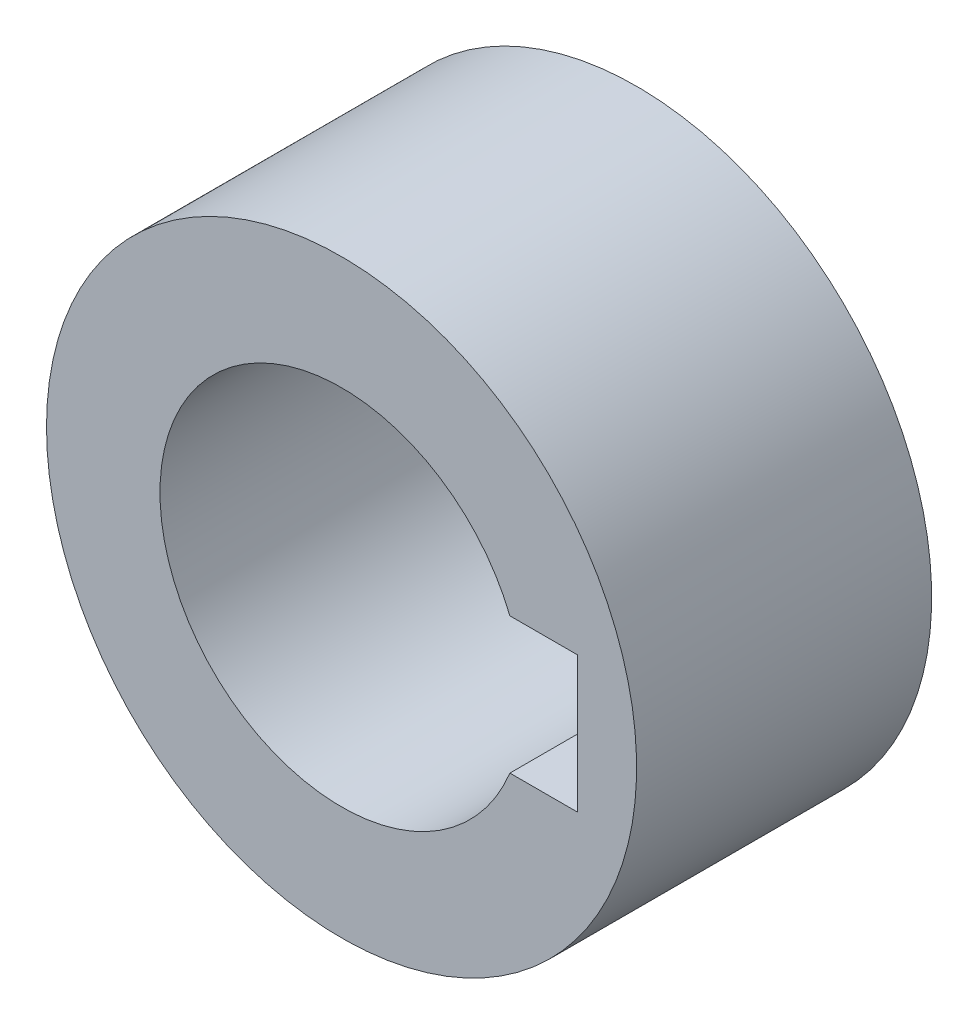
SolidWorks part; units mm, degrees
ref_plane "Front Plane" through (0, 0, 0) normal (0, 0, 1) x (1, 0, 0)
ref_plane "Top Plane" through (0, 0, 0) normal (0, 1, 0) x (1, 0, 0)
ref_plane "Right Plane" through (0, 0, 0) normal (1, 0, 0) x (0, 0, -1)
sketch "Sketch1" plane through (0, 0, 0) normal (0, 0, 1) x (1, 0, 0)
  line L0 (0, 0) -> (6.5, 0) construction
  line L1 (-4, 0) -> (-4, -1.5) construction
  line L2 (2.8, -1.5) -> (5.2, -1.5)
  line L3 (2.8, -1.5) -> (2.8, 1.5)
  line L4 (2.8, 1.5) -> (5.2, 1.5)
  line L5 (5.2, -1.5) -> (5.2, 1.5)
  line L6 (2.8, -1.5) -> (5.2, 1.5) construction
  line L7 (2.8, 1.5) -> (5.2, -1.5) construction
  circle A0 centre (0, 0) radius 4
  circle A1 centre (0, 0) radius 6.5
  point P4 (4, 0)
  dimension "D1" = 8
  dimension "D2" = 13
  dimension "D3" = 3
  dimension "D4" = 9.2
extrude "Boss-Extrude1" add sketch "Sketch1" along normal blind 6.5 contours A1 A0 L4 L5 L2
